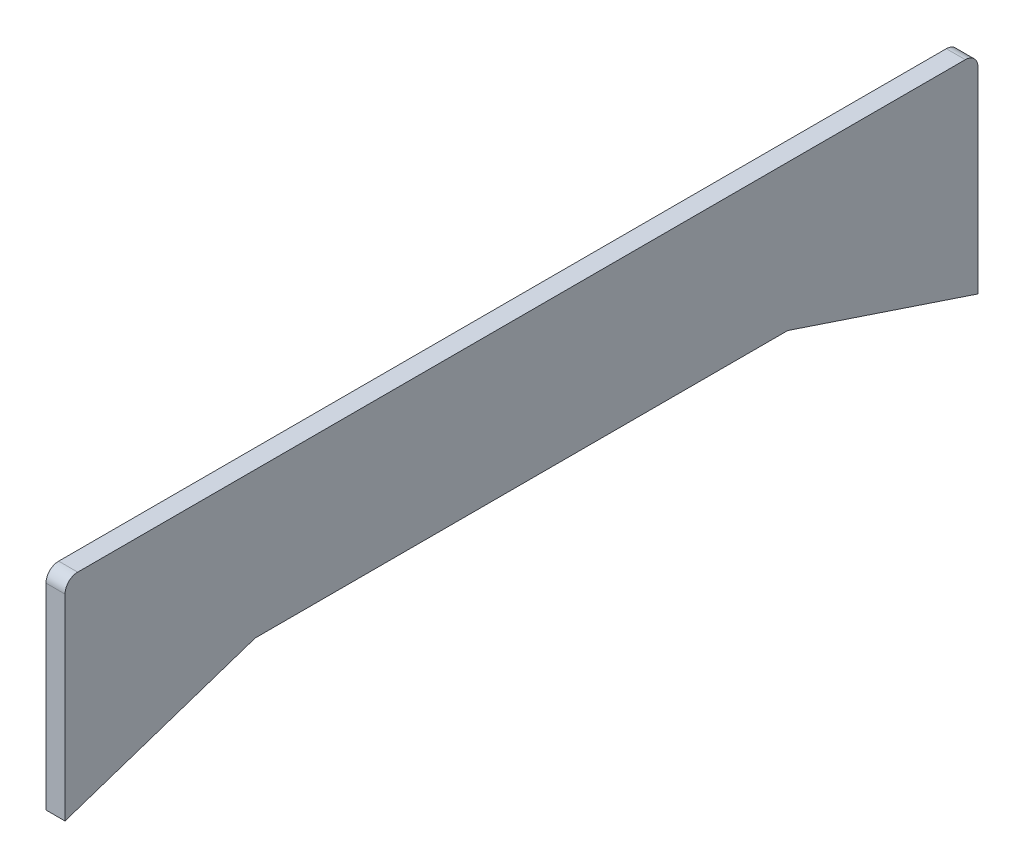
SolidWorks part; units mm, degrees
ref_plane "Front Plane" through (0, 0, 0) normal (0, 0, 1) x (1, 0, 0)
ref_plane "Top Plane" through (0, 0, 0) normal (0, 1, 0) x (1, 0, 0)
ref_plane "Right Plane" through (0, 0, 0) normal (1, 0, 0) x (0, 0, -1)
sketch "Sketch1" plane through (0, 0, 0) normal (1, 0, 0) x (0, 0, -1)
  line L1 (-72, -11.5) -> (72, -11.5)
  line L2 (-72, -11.5) -> (-72, 11.5)
  line L3 (-72, 11.5) -> (72, 11.5)
  line L4 (72, -11.5) -> (72, 11.5)
  line L5 (-72, -11.5) -> (72, 11.5) construction
  line L6 (-72, 11.5) -> (72, -11.5) construction
  point P0 (0, 0)
  dimension "D1" = 144
  dimension "D2" = 23
extrude "Boss-Extrude1" add sketch "Sketch1" along normal blind 3
fillet "Fillet1" radius 2 2 edges at (1.5, 11.5, -72) (1.5, 11.5, 72)
sketch "Sketch2" plane through (3, 0, 0) normal (1, 0, 0) x (0, 0, -1)
  line L0 (-72, -11.5) -> (-72, -21.5)
  line L1 (-72, -21.5) -> (-42, -11.5)
  line L2 (-72, -11.5) -> (72, -11.5) construction
  line L3 (72, -11.5) -> (72, -21.5)
  line L4 (72, -21.5) -> (42, -11.5)
  line L5 (-72, -11.5) -> (-42, -11.5)
  line L6 (42, -11.5) -> (72, -11.5)
  dimension "D1" = 10
  dimension "D2" = 30
  dimension "D3" = 30
  dimension "D4" = 10
extrude "Boss-Extrude2" add sketch "Sketch2" against normal blind 3
